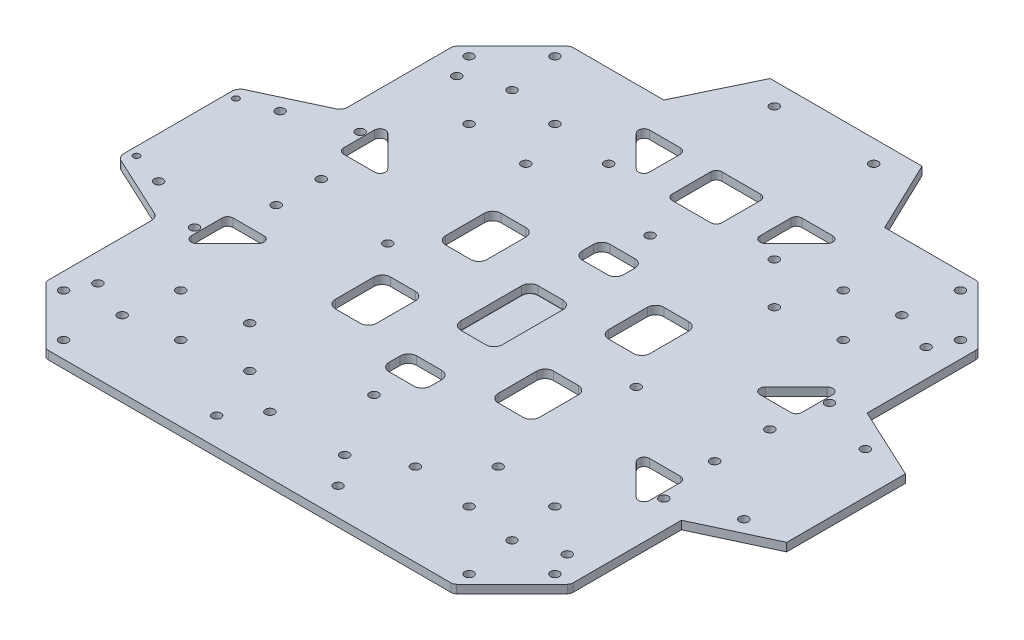
SolidWorks part; units mm, degrees
material "Thornel Mat VMA"
ref_plane "前视基准面" through (0, 0, 0) normal (0, 0, 1) x (1, 0, 0)
ref_plane "上视基准面" through (0, 0, 0) normal (0, 1, 0) x (1, 0, 0)
ref_plane "右视基准面" through (0, 0, 0) normal (1, 0, 0) x (0, 0, -1)
other "Configuration Table"
sketch "草图1" plane through (0, 0, 0) normal (0, 1, 0) x (1, 0, 0)
  line L0 (0, 0) -> (0, 165.603) construction
  line L1 (95, -73.7868) -> (95, 73.7868)
  line L2 (95, 73.7868) -> (73.7868, 95)
  line L3 (73.7868, 95) -> (-73.7868, 95)
  line L4 (-73.7868, 95) -> (-95, 73.7868)
  line L5 (-95, 73.7868) -> (-95, -73.7868)
  line L6 (-95, -73.7868) -> (-73.7868, -95)
  line L7 (-73.7868, -95) -> (73.7868, -95)
  line L8 (73.7868, -95) -> (95, -73.7868)
  line L9 (0, 0) -> (213.7391, 0) construction
  line L10 (-88.9896, -73.4332) -> (-52.22, -67.7764) construction
  line L11 (-73.4332, -88.9896) -> (-67.7764, -52.22) construction
  circle A0 centre (-88.9896, -73.4332) radius 1.6
  circle A1 centre (-73.4332, -88.9896) radius 1.6
  circle A2 centre (-73.4332, 88.9896) radius 1.6
  circle A3 centre (-88.9896, 73.4332) radius 1.6
  circle A4 centre (73.4332, 88.9896) radius 1.6
  circle A5 centre (88.9896, 73.4332) radius 1.6
  circle A6 centre (88.9896, -73.4332) radius 1.6
  circle A7 centre (73.4332, -88.9896) radius 1.6
  circle A9 centre (-67.7764, -52.22) radius 1.6
  circle A10 centre (-52.22, -67.7764) radius 1.6
  circle A11 centre (67.7764, -52.22) radius 1.6
  circle A12 centre (52.22, -67.7764) radius 1.6
  circle A13 centre (67.7764, 52.22) radius 1.6
  circle A14 centre (52.22, 67.7764) radius 1.6
  circle A15 centre (-67.7764, 52.22) radius 1.6
  circle A16 centre (-52.22, 67.7764) radius 1.6
  circle A17 centre (-70.6048, -70.6048) radius 1.6
  circle A18 centre (-70.6048, 70.6048) radius 1.6
  circle A19 centre (70.6048, -70.6048) radius 1.6
  circle A20 centre (70.6048, 70.6048) radius 1.6
  dimension "D5" = 3.2
  dimension "D6" = 3.2
  dimension "D7" = 3.2
  dimension "D1" = 190
  dimension "D2" = 190
  dimension "D3" = 30
  dimension "D4" = 135
extrude "凸台-拉伸1" add sketch "草图1" along normal blind 3 contours L8 A7 A6 L1 L2 A5 A4 L3 L4 A2 A3 L5 L6 A0 A1 L7 A15 A14 A13 A11 A10 A9 A12 A16
fillet "圆角1" radius 2 8 edges at (95, 1.5, -73.7868) (95, 1.5, 73.7868) (73.7868, 1.5, 95) (-73.7868, 1.5, 95) (-95, 1.5, -73.7868) (-73.7868, 1.5, -95) (73.7868, 1.5, -95) (-95, 1.5, 73.7868)
sketch "草图2" plane through (0, 3, 0) normal (0, 1, 0) x (1, 0, 0)
  line L0 (0, 95) -> (0, -95) construction
  line L1 (72.9584, 95) -> (-72.9584, 95) construction
  line L2 (-72.9584, -95) -> (72.9584, -95) construction
  line L3 (-20, -65) -> (-38, -83) construction
  line L4 (-38, -83) -> (-20, -83) construction
  line L5 (-20, -83) -> (-20, -65) construction
  line L6 (38, -83) -> (20, -83) construction
  line L7 (20, -65) -> (38, -83) construction
  line L8 (20, -83) -> (20, -65) construction
  line L9 (-65, 20) -> (-83, 38)
  line L10 (-9, -83) -> (9, -83) construction
  line L11 (-9, -83) -> (-9, -65) construction
  line L12 (-9, -65) -> (9, -65) construction
  line L13 (9, -83) -> (9, -65) construction
  line L14 (-83, 38) -> (-83, 20)
  line L15 (-83, 20) -> (-65, 20)
  line L16 (-83, -38) -> (-83, -20)
  line L17 (-65, -20) -> (-83, -38)
  line L18 (-83, -20) -> (-65, -20)
  line L19 (-83, 9) -> (-83, -9) construction
  line L20 (-83, 9) -> (-65, 9) construction
  line L21 (-65, 9) -> (-65, -9) construction
  line L22 (-83, -9) -> (-65, -9) construction
  line L23 (20, 65) -> (38, 83)
  line L24 (38, 83) -> (20, 83)
  line L25 (20, 83) -> (20, 65)
  line L26 (-38, 83) -> (-20, 83)
  line L27 (-20, 65) -> (-38, 83)
  line L28 (-20, 83) -> (-20, 65)
  line L29 (9, 83) -> (-9, 83)
  line L30 (9, 83) -> (9, 65)
  line L31 (9, 65) -> (-9, 65)
  line L32 (-9, 83) -> (-9, 65)
  line L33 (65, -20) -> (83, -38)
  line L34 (83, -38) -> (83, -20)
  line L35 (83, -20) -> (65, -20)
  line L36 (83, 38) -> (83, 20)
  line L37 (65, 20) -> (83, 38)
  line L38 (83, 20) -> (65, 20)
  line L39 (83, -9) -> (83, 9) construction
  line L40 (83, -9) -> (65, -9) construction
  line L41 (65, -9) -> (65, 9) construction
  line L42 (83, 9) -> (65, 9) construction
  point P49 (0, 0)
  dimension "D1" = 20
  dimension "D2" = 18
  dimension "D3" = 12
  dimension "D4" = 11
  dimension "D5" = 4
extrude "切除-拉伸1" cut sketch "草图2" against normal through all
fillet "圆角2" radius 2 22 edges at (38, 1.5, -83) (20, 1.5, -65) (20, 1.5, -83) (-20, 1.5, -83) (-20, 1.5, -65) (-38, 1.5, -83) (-9, 1.5, -65) (-9, 1.5, -83) (9, 1.5, -83) (9, 1.5, -65) (-83, 1.5, 20) (-65, 1.5, 20) (-83, 1.5, -38) (-65, 1.5, -20) (-83, 1.5, -20) (83, 1.5, -20) (65, 1.5, -20) (83, 1.5, -38) (83, 1.5, 38) (65, 1.5, 20) (83, 1.5, 20) (-83, 1.5, 38)
sketch "草图4" plane through (0, 3, 0) normal (0, 1, 0) x (1, 0, 0)
  line L0 (0, 0) -> (0, 123) construction
  line L1 (72.9584, 95) -> (-72.9584, 95) construction
  line L2 (-21.5, 121) -> (-33.624, 95) construction
  line L3 (-21.5, 95) -> (21.5, 95) construction
  line L5 (-21.5, 121) -> (21.5, 121) construction
  line L7 (-33.624, 95) -> (-21.5, 95) construction
  line L8 (21.5, 121) -> (33.624, 95) construction
  line L9 (33.624, 95) -> (21.5, 95) construction
  line L16 (21.5, -121) -> (33.624, -95) construction
  line L17 (21.5, -95) -> (-21.5, -95) construction
  line L18 (21.5, -121) -> (-21.5, -121) construction
  line L19 (33.624, -95) -> (21.5, -95) construction
  line L20 (-21.5, -121) -> (-33.624, -95) construction
  line L21 (-33.624, -95) -> (-21.5, -95) construction
  line L22 (-121, -21.5) -> (-95, -33.624)
  line L23 (-95, -21.5) -> (-95, 21.5)
  line L24 (-121, -21.5) -> (-121, 21.5)
  line L25 (-95, -33.624) -> (-95, -21.5)
  line L26 (-121, 21.5) -> (-95, 33.624)
  line L27 (-95, 33.624) -> (-95, 21.5)
  line L28 (121, 21.5) -> (95, 33.624) [skipped]
  line L29 (95, 21.5) -> (95, -21.5) [skipped]
  line L30 (121, 21.5) -> (121, -21.5) [skipped]
  line L31 (95, 33.624) -> (95, 21.5) [skipped]
  line L32 (121, -21.5) -> (95, -33.624) [skipped]
  line L33 (95, -33.624) -> (95, -21.5) [skipped]
  line L34 (95, 33.624) -> (95, 21.5)
  line L36 (121, 21.5) -> (95, 33.624)
  line L37 (95, -33.624) -> (95, -21.5)
  line L38 (121, -21.5) -> (121, 21.5)
  line L39 (95, -21.5) -> (95, 21.5)
  line L40 (121, -21.5) -> (95, -33.624)
  point P32 (0, 0)
  dimension "D1" = 28
  dimension "D2" = 43
  dimension "D3" = 26
  dimension "D4" = 65
  dimension "D5" = 26
  dimension "D6" = 4
extrude "凸台-拉伸2" add sketch "草图4" against normal up to surface (3 mm away) up to face at (77.4291, 0, -25.5709)
fillet "圆角3" radius 3 4 edges at (-121, 1.5, -21.5) (-121, 1.5, 21.5) (-95, 1.5, 33.624) (-95, 1.5, -33.624)
sketch "草图5" plane through (0, 0, 0) normal (0, -1, 0) x (1, 0, 0)
  line L0 (0, -121) -> (0, 0) construction
  line L3 (-21, -121) -> (21, -121) construction
  line L4 (-21, -121) -> (-21, -79) construction
  line L5 (-21, -79) -> (21, -79) construction
  line L6 (21, -121) -> (21, -79) construction
  line L46 (77.5, 0) -> (-77.5, 0) construction
  line L47 (-37, -10) -> (-22, -10)
  line L48 (-77.25, 8.16) -> (-46.75, 8.16) construction
  line L65 (-77.25, 8.16) -> (-77.25, -8.16) construction
  line L66 (-77.25, -8.16) -> (-46.75, -8.16) construction
  line L67 (-46.75, 8.16) -> (-46.75, -8.16) construction
  line L68 (-7.5, -14) -> (7.5, -14)
  line L69 (-62, 9) -> (-62, -9) construction
  line L71 (72.9584, -95) -> (-72.9584, -95) construction
  line L72 (-7.5, -14) -> (-7.5, 14)
  line L73 (-7.5, 14) -> (7.5, 14)
  line L74 (7.5, -14) -> (7.5, 14)
  line L75 (-7.5, -14) -> (7.5, 14) construction
  line L76 (-7.5, 14) -> (7.5, -14) construction
  line L77 (-37, 30) -> (-22, 30)
  line L78 (-37, 30) -> (-37, 10)
  line L79 (-37, 10) -> (-22, 10)
  line L80 (-22, 30) -> (-22, 10)
  line L81 (-22, -30) -> (-22, -10)
  line L82 (-37, -30) -> (-22, -30)
  line L83 (-37, -30) -> (-37, -10)
  line L84 (37, 10) -> (22, 10)
  line L85 (22, 30) -> (22, 10)
  line L86 (37, 30) -> (22, 30)
  line L87 (37, 30) -> (37, 10)
  line L88 (37, -30) -> (37, -10)
  line L89 (37, -30) -> (22, -30)
  line L90 (22, -30) -> (22, -10)
  line L91 (37, -10) -> (22, -10)
  line L92 (-7.5, -40) -> (7.5, -40)
  line L93 (-7.5, 30) -> (7.5, 30)
  line L94 (-7.5, 30) -> (-7.5, 40)
  line L95 (-7.5, 40) -> (7.5, 40)
  line L96 (7.5, 30) -> (7.5, 40)
  line L97 (-7.5, 30) -> (7.5, 40) construction
  line L98 (-7.5, 40) -> (7.5, 30) construction
  line L99 (7.5, -30) -> (7.5, -40)
  line L100 (-7.5, -30) -> (7.5, -30)
  line L101 (-7.5, -30) -> (-7.5, -40)
  line L102 (0, 95) -> (0, 52.1919) construction
  line L103 (-72.9584, 95) -> (72.9584, 95) construction
  line L104 (13.55, 74.15) -> (-13.55, 74.15) construction
  circle A0 centre (-10.8959, -82.5) radius 1.6 construction
  circle A1 centre (9.1041, -82.5) radius 1.6 construction
  circle A2 centre (22, -106) radius 1.6 construction
  circle A3 centre (-22, -106) radius 1.6 construction
  circle A60 centre (-106, 22) radius 1.6
  circle A61 centre (-82.5, 10.8959) radius 1.6 construction
  circle A62 centre (-82.5, -9.1041) radius 1.6 construction
  circle A63 centre (-106, -22) radius 1.6
  circle A64 centre (22, 106) radius 1.6 construction
  circle A65 centre (10.8959, 82.5) radius 1.6 construction
  circle A66 centre (-9.1041, 82.5) radius 1.6 construction
  circle A67 centre (-22, 106) radius 1.6 construction
  circle A68 centre (106, -22) radius 1.6
  circle A69 centre (82.5, -10.8959) radius 1.6 construction
  circle A70 centre (82.5, 9.1041) radius 1.6 construction
  circle A71 centre (106, 22) radius 1.6
  circle A72 centre (-82.5, 10.8959) radius 1.6 construction
  circle A73 centre (-82.5, -9.1041) radius 1.6 construction
  circle A74 centre (10.8959, 82.5) radius 1.6 construction
  circle A75 centre (-9.1041, 82.5) radius 1.6 construction
  circle A76 centre (82.5, -10.8959) radius 1.6
  circle A77 centre (82.5, 9.1041) radius 1.6
  circle A78 centre (-77.25, 8.16) radius 1.6
  circle A79 centre (-46.75, 8.16) radius 1.6 construction
  circle A80 centre (-46.75, -8.16) radius 1.6 construction
  circle A81 centre (-77.25, -8.16) radius 1.6
  circle A82 centre (13.55, 74.15) radius 1.6
  circle A83 centre (-13.55, 74.15) radius 1.6
  point P2 (0, 74.15)
  point P32 (0, 35)
  point P156 (0, 0)
  point P169 (0, 0)
  dimension "D1" = 3.2
  dimension "D5" = 15
  dimension "D6" = 3.2
  dimension "D10" = 3.2
  dimension "D11" = 3.2
  dimension "D2" = 42
  dimension "D3" = 42
  dimension "D4" = 22
  dimension "D9" = 30.5
  dimension "D12" = 15
  dimension "D13" = 28
  dimension "D14" = 15
  dimension "D15" = 20
  dimension "D16" = 22
  dimension "D17" = 10
  dimension "D18" = 16
  dimension "D19" = 10
  dimension "D20" = 15
  dimension "D21" = 18
  dimension "D22" = 62
  dimension "D23" = 16.32
  dimension "D24" = 26
  dimension "D25" = 27.1
  dimension "D26" = 20.85
  dimension "D7" = 4
  dimension "D8" = 4
extrude "切除-拉伸3" cut sketch "草图5" against normal blind 10
fillet "圆角4" radius 3 28 edges at (-7.5, 1.5, -30) (7.5, 1.5, -30) (7.5, 1.5, -40) (-7.5, 1.5, -40) (22, 1.5, -30) (22, 1.5, -10) (37, 1.5, -10) (37, 1.5, -30) (7.5, 1.5, -14) (-7.5, 1.5, -14) (-7.5, 1.5, 14) (7.5, 1.5, 14) (7.5, 1.5, 30) (-7.5, 1.5, 30) (-7.5, 1.5, 40) (7.5, 1.5, 40) (-22, 1.5, 30) (-22, 1.5, 10) (-37, 1.5, 10) (-37, 1.5, -10) (-22, 1.5, -10) (-22, 1.5, -30) (-37, 1.5, -30) (37, 1.5, 10) (22, 1.5, 10) (22, 1.5, 30) (37, 1.5, 30) (-37, 1.5, 30)
sketch "草图6" plane through (0, 0, 0) normal (0, -1, 0) x (1, 0, 0)
  line L0 (-118, 18) -> (-118, -18) construction
  line L2 (-121, 0) -> (-102.1382, 0) construction
  line L4 (-121, 19.5888) -> (-121, -19.5888) construction
  circle A0 centre (-118, 18) radius 1.15
  circle A1 centre (-118, -18) radius 1.15
  point P7 (-118, 0)
  dimension "D2" = 2.3
  dimension "D1" = 36
  dimension "D3" = 3
extrude "激光安装孔" cut sketch "草图6" against normal blind 10
sketch "草图7" plane through (0, 3, 0) normal (0, 1, 0) x (1, 0, 0)
  line L0 (-40, 95) -> (-27.5, 121)
  line L1 (72.9584, 95) -> (-72.9584, 95) construction
  line L2 (-27.5, 121) -> (27.5, 121)
  line L3 (27.5, 121) -> (40, 95)
  line L4 (-40, 95) -> (40, 95)
  line L5 (0, 0) -> (0, 95) construction
  line L6 (0, 95) -> (0, 121) construction
  line L7 (18, 113) -> (-18, 113) construction
  circle A0 centre (18, 113) radius 1.6
  circle A1 centre (-18, 113) radius 1.6
  dimension "D5" = 3.2
  dimension "D1" = 80
  dimension "D2" = 55
  dimension "D3" = 26
  dimension "D4" = 36
  dimension "D6" = 8
extrude "凸台-拉伸3" add sketch "草图7" against normal up to surface (3 mm away) up to face at (-118, 0, 16.85)
sketch "草图8" plane through (0, 0, 0) normal (0, -1, 0) x (1, 0, 0)
  line L0 (0, 95) -> (0, 33.0191) construction
  line L2 (22, 85) -> (-22, 85) construction
  line L3 (-72.9584, 95) -> (72.9584, 95) construction
  circle A0 centre (22, 85) radius 1.6
  circle A1 centre (-22, 85) radius 1.6
  point P7 (0, 85)
  dimension "D1" = 44
  dimension "D2" = 3.2
  dimension "D3" = 10
extrude "切除-拉伸4" cut sketch "草图8" against normal blind 40
sketch "草图9" plane through (0, 0, 0) normal (0, -1, 0) x (1, 0, 0)
  line L1 (-45, 50) -> (45, 50) construction
  line L2 (-45, 50) -> (-45, -50) construction
  line L3 (-45, -50) -> (45, -50) construction
  line L4 (45, 50) -> (45, -50) construction
  line L5 (-45, 50) -> (45, -50) construction
  line L6 (-45, -50) -> (45, 50) construction
  circle A0 centre (-45, -50) radius 1.6
  circle A1 centre (45, -50) radius 1.6
  circle A2 centre (0, -50) radius 1.6
  circle A3 centre (-45, 0) radius 1.6
  circle A4 centre (-45, 50) radius 1.6
  circle A5 centre (0, 50) radius 1.6
  circle A6 centre (45, 50) radius 1.6
  circle A8 centre (45, 0) radius 1.6
  circle A9 centre (85, 65) radius 1.6 construction
  circle A10 centre (85, 65) radius 1.6
  circle A11 centre (-85, 65) radius 1.6 construction
  circle A12 centre (-85, 65) radius 1.6
  circle A13 centre (-85, -65) radius 1.6 construction
  circle A14 centre (-85, -65) radius 1.6
  circle A15 centre (85, -65) radius 1.6 construction
  circle A16 centre (85, -65) radius 1.6
  circle A17 centre (30, -65) radius 1.6 construction
  circle A18 centre (30, -65) radius 1.6
  circle A19 centre (-30, -65) radius 1.6 construction
  circle A20 centre (-30, -65) radius 1.6
  circle A21 centre (30, 65) radius 1.6 construction
  circle A22 centre (30, 65) radius 1.6
  circle A23 centre (-30, 65) radius 1.6 construction
  circle A24 centre (-30, 65) radius 1.6
  circle A25 centre (85, 30) radius 1.6 construction
  circle A26 centre (85, 30) radius 1.6
  circle A27 centre (85, -30) radius 1.6 construction
  circle A28 centre (85, -30) radius 1.6
  circle A29 centre (-85, -30) radius 1.6 construction
  circle A30 centre (-85, -30) radius 1.6
  circle A31 centre (-85, 30) radius 1.6 construction
  circle A32 centre (-85, 30) radius 1.6
  point P0 (0, 0)
  dimension "D3" = 3.2
  dimension "D1" = 90
  dimension "D2" = 100
extrude "切除-拉伸5" cut sketch "草图9" against normal blind 10
sketch "草图10" plane through (0, 0, 0) normal (0, -1, 0) x (1, 0, 0)
  line L0 (4.5, 13.9) -> (-4.5, 13.9)
  line L1 (-7.4, 11) -> (-7.4, -11)
  line L2 (-4.5, -13.9) -> (4.5, -13.9)
  line L3 (7.4, -11) -> (7.4, 11)
  line L4 (4.5, 14) -> (-4.5, 14)
  line L5 (7.5, -11) -> (7.5, 11)
  line L6 (-4.5, -14) -> (4.5, -14)
  line L7 (-7.5, 11) -> (-7.5, -11)
  line L8 (4.5, 14) -> (-4.5, 14)
  line L9 (7.5, -11) -> (7.5, 11)
  line L10 (-4.5, -14) -> (4.5, -14)
  line L11 (-7.5, 11) -> (-7.5, -11)
  arc A0 (-4.5, 13.9) -> (-7.4, 11) centre (-4.5, 11) ccw
  arc A1 (-7.4, -11) -> (-4.5, -13.9) centre (-4.5, -11) ccw
  arc A2 (4.5, -13.9) -> (7.4, -11) centre (4.5, -11) ccw
  arc A3 (7.4, 11) -> (4.5, 13.9) centre (4.5, 11) ccw
  arc A4 (7.5, 11) -> (4.5, 14) centre (4.5, 11) ccw
  arc A5 (4.5, -14) -> (7.5, -11) centre (4.5, -11) ccw
  arc A6 (-7.5, -11) -> (-4.5, -14) centre (-4.5, -11) ccw
  arc A7 (-4.5, 14) -> (-7.5, 11) centre (-4.5, 11) ccw
  arc A8 (7.5, 11) -> (4.5, 14) centre (4.5, 11) ccw
  arc A9 (4.5, -14) -> (7.5, -11) centre (4.5, -11) ccw
  arc A10 (-7.5, -11) -> (-4.5, -14) centre (-4.5, -11) ccw
  arc A11 (-4.5, 14) -> (-7.5, 11) centre (-4.5, 11) ccw
  dimension "D1" = 0
  dimension "D2" = 0.1
extrude "凸台-拉伸4" add sketch "草图10" along normal blind 3 separate body contours L3 A3 L0 A0 L1 A1 L2 A2
sketch "草图11" plane through (0, -3, 0) normal (0, -1, 0) x (1, 0, 0)
  line L1 (-12.5, 17.5) -> (12.5, 17.5)
  line L2 (-12.5, 17.5) -> (-12.5, -17.5)
  line L3 (-12.5, -17.5) -> (12.5, -17.5)
  line L4 (12.5, 17.5) -> (12.5, -17.5)
  line L5 (-12.5, 17.5) -> (12.5, -17.5) construction
  line L6 (-12.5, -17.5) -> (12.5, 17.5) construction
  point P0 (0, 0)
  dimension "D1" = 25
  dimension "D2" = 35
extrude "凸台-拉伸5" add sketch "草图11" along normal blind 3
fillet "圆角5" radius 3 4 edges at (12.5, -4.5, 17.5) (-12.5, -4.5, 17.5) (12.5, -4.5, -17.5) (-12.5, -4.5, -17.5)
